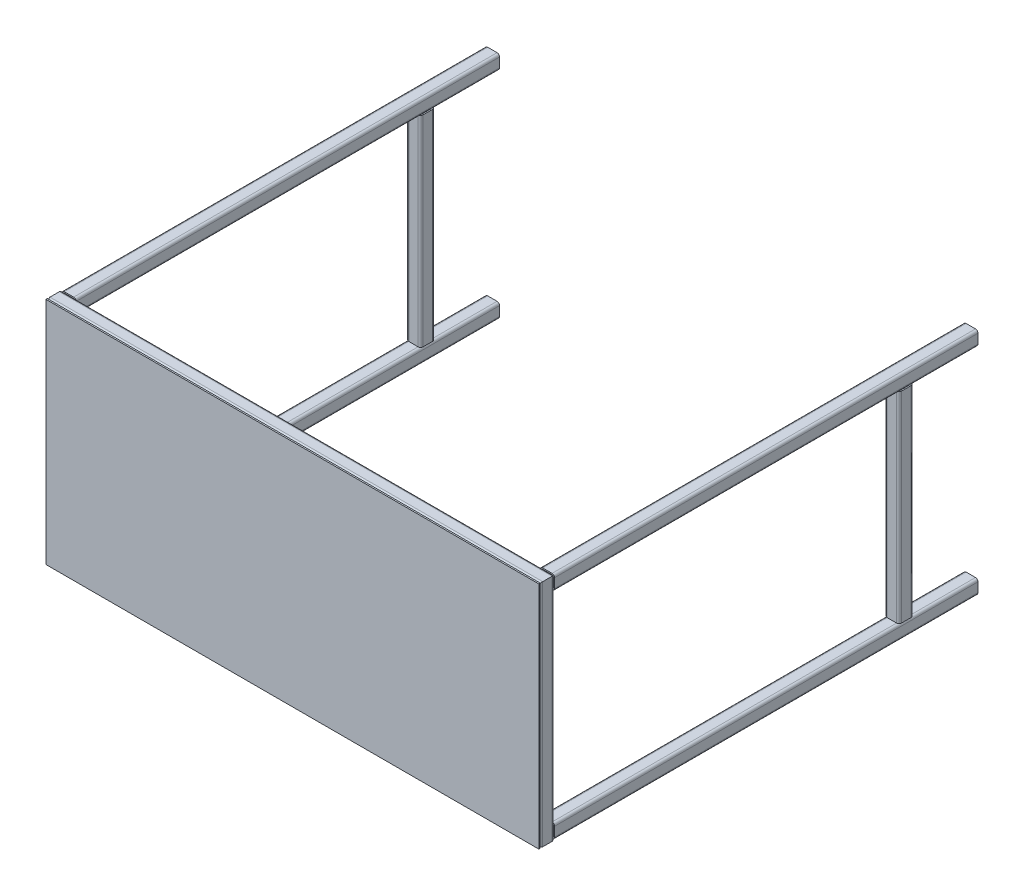
SolidWorks part; units mm, degrees
material "Q235A"
ref_plane "前视" through (0, 0, 0) normal (0, 0, 1) x (1, 0, 0)
ref_plane "上视" through (0, 0, 0) normal (0, 1, 0) x (1, 0, 0)
ref_plane "右视" through (0, 0, 0) normal (1, 0, 0) x (0, 0, -1)
sketch "草图1" plane through (0, 0, 0) normal (0, 0, 1) x (1, 0, 0)
  line L1 (500, -225) -> (-500, -225)
  line L2 (500, -225) -> (500, 225)
  line L3 (500, 225) -> (-500, 225)
  line L4 (-500, -225) -> (-500, 225)
  line L5 (500, -225) -> (-500, 225) construction
  line L6 (500, 225) -> (-500, -225) construction
  line L7 (500, -225) -> (-500, -225)
  line L8 (500, -225) -> (500, 225)
  line L9 (500, 225) -> (-500, 225)
  line L10 (-500, -225) -> (-500, 225)
  line L11 (500, -225) -> (-500, 225) construction
  line L12 (500, 225) -> (-500, -225) construction
  point P0 (0, 0)
  point P6 (0, 0)
  dimension "D1" = 1000
  dimension "D2" = 450
ref_plane "基准面1" through (500, 0, 0) normal (1, 0, 0) x (0, 0, -1)
ref_plane "基准面2" through (-500, 0, 0) normal (1, 0, 0) x (0, 0, -1)
sketch "草图2" plane through (500, 0, 0) normal (1, 0, 0) x (0, 0, -1)
  line L0 (0, 225) -> (900, 225)
  line L1 (0, -225) -> (0, 225) construction
  line L2 (0, -225) -> (900, -225)
  line L3 (0, 225) -> (0, -225) construction
  line L4 (0, -225) -> (0, 225) construction
  dimension "D1" = 900
sketch "草图3" plane through (-500, 0, 0) normal (1, 0, 0) x (0, 0, -1)
  line L0 (0, 225) -> (900, 225)
  line L1 (0, -225) -> (900, -225)
other "结构构件1"
ref_plane "基准面3" through (500, -225, 0) normal (0, 1, 0) x (-1, 0, 0)
sketch "Sketch1" plane through (500, -225, 0) normal (0, 1, 0) x (-1, 0, 0)
  line L0 (-9.8, -12.4) -> (9.8, -12.4)
  line L1 (-12.4, -9.8) -> (-12.4, 9.8)
  line L2 (9.8, 12.4) -> (-9.8, 12.4)
  line L3 (12.4, 9.8) -> (12.4, -9.8)
  line L4 (-9.8, -15) -> (9.8, -15)
  line L5 (-15, -9.8) -> (-15, 9.8)
  line L6 (9.8, 15) -> (-9.8, 15)
  line L7 (15, 9.8) -> (15, -9.8)
  arc A0 (15, 9.8) -> (9.8, 15) centre (9.8, 9.8) ccw
  arc A1 (9.8, -15) -> (15, -9.8) centre (9.8, -9.8) ccw
  arc A2 (-15, -9.8) -> (-9.8, -15) centre (-9.8, -9.8) ccw
  arc A3 (-9.8, 15) -> (-15, 9.8) centre (-9.8, 9.8) ccw
  arc A4 (-9.8, 12.4) -> (-12.4, 9.8) centre (-9.8, 9.8) ccw
  arc A5 (12.4, 9.8) -> (9.8, 12.4) centre (9.8, 9.8) ccw
  arc A6 (9.8, -12.4) -> (12.4, -9.8) centre (9.8, -9.8) ccw
  arc A7 (-12.4, -9.8) -> (-9.8, -12.4) centre (-9.8, -9.8) ccw
  point P0 (-15, 0)
  point P1 (15, 0)
  point P2 (0, 15)
  point P3 (0, -15)
  point P4 (0, 0)
  point P5 (-15, -15)
  point P6 (15, -15)
  point P7 (15, 15)
  point P8 (-15, 15)
  point P33 (0, 0)
  dimension "D1" = 5.2
  dimension "Thickness" = 2.6
  dimension "V_leg" = 30
other "结构构件2"
ref_plane "基准面4" through (500, 225, 0) normal (0, 0, -1) x (0, 1, 0)
sketch "Sketch11" plane through (500, 225, 0) normal (0, 0, -1) x (0, 1, 0)
  line L0 (-9.8, -12.4) -> (9.8, -12.4)
  line L1 (-12.4, -9.8) -> (-12.4, 9.8)
  line L2 (9.8, 12.4) -> (-9.8, 12.4)
  line L3 (12.4, 9.8) -> (12.4, -9.8)
  line L4 (-9.8, -15) -> (9.8, -15)
  line L5 (-15, -9.8) -> (-15, 9.8)
  line L6 (9.8, 15) -> (-9.8, 15)
  line L7 (15, 9.8) -> (15, -9.8)
  arc A0 (15, 9.8) -> (9.8, 15) centre (9.8, 9.8) ccw
  arc A1 (9.8, -15) -> (15, -9.8) centre (9.8, -9.8) ccw
  arc A2 (-15, -9.8) -> (-9.8, -15) centre (-9.8, -9.8) ccw
  arc A3 (-9.8, 15) -> (-15, 9.8) centre (-9.8, 9.8) ccw
  arc A4 (-9.8, 12.4) -> (-12.4, 9.8) centre (-9.8, 9.8) ccw
  arc A5 (12.4, 9.8) -> (9.8, 12.4) centre (9.8, 9.8) ccw
  arc A6 (9.8, -12.4) -> (12.4, -9.8) centre (9.8, -9.8) ccw
  arc A7 (-12.4, -9.8) -> (-9.8, -12.4) centre (-9.8, -9.8) ccw
  point P0 (-15, 0)
  point P1 (15, 0)
  point P2 (0, 15)
  point P3 (0, -15)
  point P4 (0, 0)
  point P5 (-15, -15)
  point P6 (15, -15)
  point P7 (15, 15)
  point P8 (-15, 15)
  point P33 (0, 0)
  dimension "D1" = 5.2
  dimension "Thickness" = 2.6
  dimension "V_leg" = 30
other "剪裁/延伸1"
sketch "草图6" plane through (0, 0, 15) normal (0, 0, 1) x (1, 0, 0)
  line L1 (515, -240) -> (-515, -240)
  line L2 (515, -240) -> (515, 240)
  line L3 (515, 240) -> (-515, 240)
  line L4 (-515, -240) -> (-515, 240)
  line L5 (515, -240) -> (-515, 240) construction
  line L6 (515, 240) -> (-515, -240) construction
  point P0 (0, 0)
extrude "凸台-拉伸1" add sketch "草图6" along normal blind 3 separate body
sketch "草图7" plane through (-500, 0, 0) normal (1, 0, 0) x (0, 0, -1)
  line L0 (750, 225) -> (750, -225)
  line L1 (0, 225) -> (900, 225) construction
  line L2 (0, -225) -> (900, -225) construction
  dimension "D1" = 150
sketch "草图8" plane through (500, 0, 0) normal (1, 0, 0) x (0, 0, -1)
  line L0 (750, 225) -> (750, -225)
other "结构构件3"
ref_plane "基准面5" through (500, 225, -750) normal (0, -1, 0) x (0, 0, -1)
sketch "Sketch12" plane through (500, 225, -750) normal (0, -1, 0) x (0, 0, -1)
  line L0 (-9.8, -12.4) -> (9.8, -12.4)
  line L1 (-12.4, -9.8) -> (-12.4, 9.8)
  line L2 (9.8, 12.4) -> (-9.8, 12.4)
  line L3 (12.4, 9.8) -> (12.4, -9.8)
  line L4 (-9.8, -15) -> (9.8, -15)
  line L5 (-15, -9.8) -> (-15, 9.8)
  line L6 (9.8, 15) -> (-9.8, 15)
  line L7 (15, 9.8) -> (15, -9.8)
  arc A0 (15, 9.8) -> (9.8, 15) centre (9.8, 9.8) ccw
  arc A1 (9.8, -15) -> (15, -9.8) centre (9.8, -9.8) ccw
  arc A2 (-15, -9.8) -> (-9.8, -15) centre (-9.8, -9.8) ccw
  arc A3 (-9.8, 15) -> (-15, 9.8) centre (-9.8, 9.8) ccw
  arc A4 (-9.8, 12.4) -> (-12.4, 9.8) centre (-9.8, 9.8) ccw
  arc A5 (12.4, 9.8) -> (9.8, 12.4) centre (9.8, 9.8) ccw
  arc A6 (9.8, -12.4) -> (12.4, -9.8) centre (9.8, -9.8) ccw
  arc A7 (-12.4, -9.8) -> (-9.8, -12.4) centre (-9.8, -9.8) ccw
  point P0 (-15, 0)
  point P1 (15, 0)
  point P2 (0, 15)
  point P3 (0, -15)
  point P4 (0, 0)
  point P5 (-15, -15)
  point P6 (15, -15)
  point P7 (15, 15)
  point P8 (-15, 15)
  point P33 (0, 0)
  dimension "D1" = 5.2
  dimension "Thickness" = 2.6
  dimension "V_leg" = 30
other "剪裁/延伸2"
